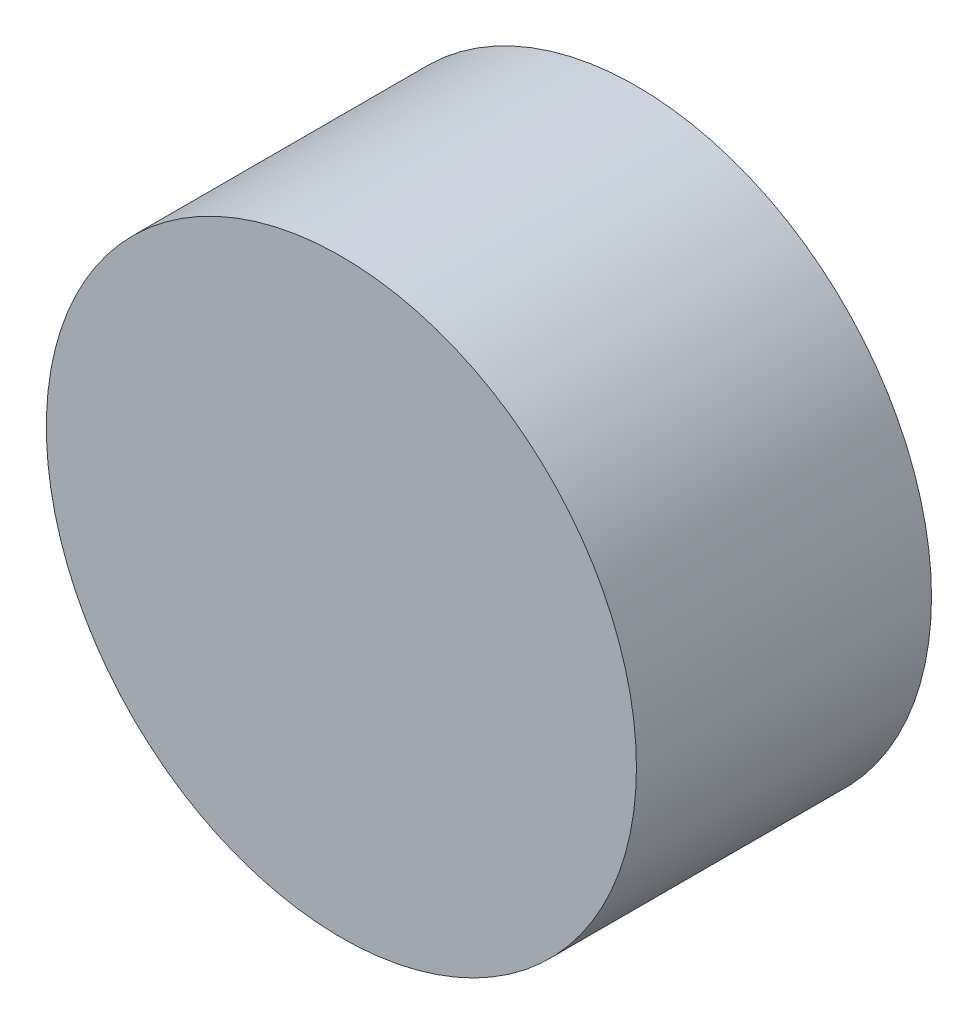
SolidWorks part; units mm, degrees
ref_plane "前视基准面" through (0, 0, 0) normal (0, 0, 1) x (1, 0, 0)
ref_plane "上视基准面" through (0, 0, 0) normal (0, 1, 0) x (1, 0, 0)
ref_plane "右视基准面" through (0, 0, 0) normal (1, 0, 0) x (0, 0, -1)
other "Configuration Table"
sketch "草图1" plane through (0, 0, 0) normal (0, 0, 1) x (1, 0, 0)
  circle A0 centre (0, 0) radius 4
  dimension "diameter" = 8
extrude "Pitch_Pivot" add sketch "草图1" along normal blind 4
